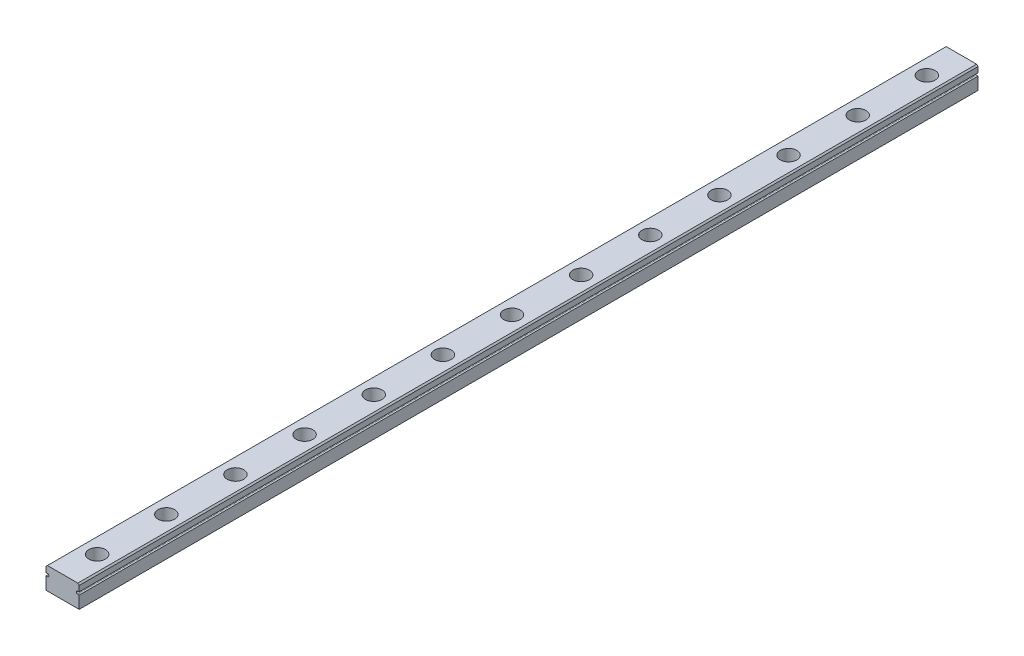
SolidWorks part; units mm, degrees
material "Stainless Steel (ferritic)"
ref_plane "Front Plane" through (0, 0, 0) normal (0, 0, 1) x (1, 0, 0)
ref_plane "Top Plane" through (0, 0, 0) normal (0, 1, 0) x (1, 0, 0)
ref_plane "Right Plane" through (0, 0, 0) normal (1, 0, 0) x (0, 0, -1)
sketch "Sketch1" plane through (0, 0, 0) normal (0, 0, 1) x (1, 0, 0)
  line L0 (-6, 1.5) -> (-5.4, 1.5)
  line L1 (-5.5, 4) -> (5.5, 4)
  line L2 (-6, 3.5) -> (-6, 1.5)
  line L3 (-6, -4) -> (6, -4)
  line L4 (6, 3.5) -> (6, 1.5)
  line L5 (-6, 4) -> (6, -4) construction
  line L6 (-6, -4) -> (6, 4) construction
  line L7 (-5, 1.1) -> (-5, 0.9)
  line L8 (-5.4, 0.5) -> (-6, 0.5)
  line L9 (6, 0.5) -> (5.4, 0.5)
  line L10 (5, 0.9) -> (5, 1.1)
  line L11 (5.4, 1.5) -> (6, 1.5)
  line L12 (-6, 0.5) -> (-6, -4)
  line L13 (6, 0.5) -> (6, -4)
  line L14 (-5.5, 4) -> (-6, 3.5)
  line L15 (5.5, 4) -> (6, 3.5)
  arc A0 (-5, 0.9) -> (-5.4, 0.5) centre (-5.4, 0.9) cw
  arc A1 (-5.4, 1.5) -> (-5, 1.1) centre (-5.4, 1.1) cw
  arc A2 (5, 1.1) -> (5.4, 1.5) centre (5.4, 1.1) cw
  arc A3 (5, 0.9) -> (5.4, 0.5) centre (5.4, 0.9) ccw
  point P0 (0, 0)
  point P12 (-5, 0.5)
  point P15 (-5, 1.5)
  point P24 (5, 0.5)
  dimension "D6" = 0.4
  dimension "D8" = 0.4
  dimension "D1" = 12
  dimension "D2" = 8
  dimension "D3" = 4.5
  dimension "D4" = 1
  dimension "D5" = 1
  dimension "D7" = 1
extrude "Boss-Extrude1" add sketch "Sketch1" along normal blind 325
sketch "Sketch3" plane through (0, 4, 0) normal (0, 1, 0) x (1, 0, 0)
  line L0 (5.5, -325) -> (-5.5, -325) construction
  circle A0 centre (0, -312.5) radius 1.5
  dimension "D1" = 12.5
  dimension "D2" = 3
extrude "Cut-Extrude1" cut sketch "Sketch3" against normal blind 14
sketch "Sketch4" plane through (0, 4, 0) normal (0, 1, 0) x (1, 0, 0)
  circle A0 centre (0, -312.5) radius 3
  dimension "D1" = 6
extrude "Cut-Extrude2" cut sketch "Sketch4" against normal blind 4.5
pattern_linear "LPattern2" count 14 spacing 25 along (0, 0, -1) of "Cut-Extrude2", "Cut-Extrude1"
